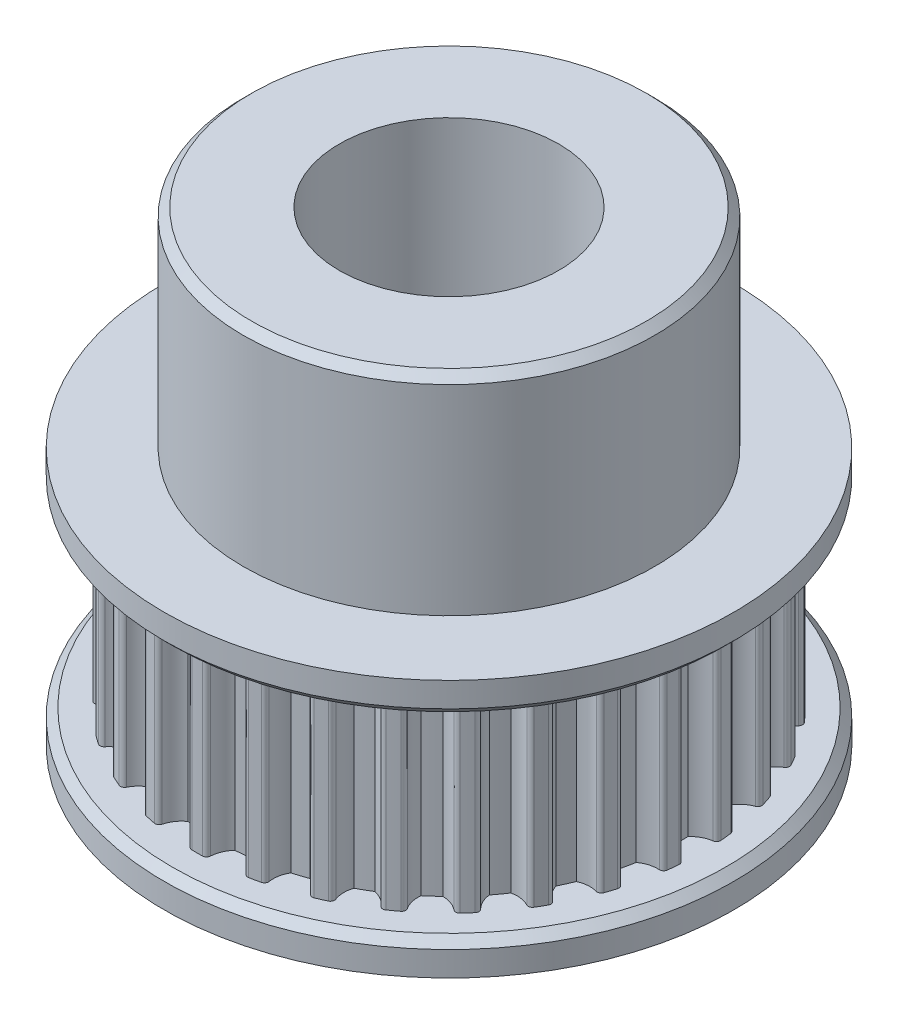
SolidWorks part; units mm, degrees
ref_plane "Front Plane" through (0, 0, 0) normal (0, 0, 1) x (1, 0, 0)
ref_plane "Top Plane" through (0, 0, 0) normal (0, 1, 0) x (1, 0, 0)
ref_plane "Right Plane" through (0, 0, 0) normal (1, 0, 0) x (0, 0, -1)
sketch "Sketch1" plane through (0, 0, 0) normal (0, 1, 0) x (1, 0, 0)
  line L0 (0, 0) -> (0, 9.44) construction
  line L1 (0, 0) -> (0.9867, 9.3883) construction
  line L2 (0, 0) -> (1.379, 9.3387) construction
  circle A0 centre (0, 0) radius 9.44 construction
  circle A1 centre (0, 0) radius 8.436 construction
  circle A2 centre (0, 0) radius 9.186 construction
  arc A3 (0.8818, 8.3898) -> (0.418, 8.7527) centre (0.9398, 8.9417) cw
  arc A4 (2.2821, 9.4281) -> (0.343, 9.0409) centre (1.3419, 9.0875) cw
  circle A5 centre (0, 0) radius 9.036 construction
  arc A6 (-0.1964, 9.1839) -> (0.1964, 9.1839) centre (0, 0) cw
  arc A7 (0.1964, 9.1839) -> (0.343, 9.0409) centre (0.1932, 9.0339) cw
  arc A8 (2.2821, 9.4281) -> (0.418, 8.7527) centre (1.3501, 9.0904) ccw
  arc A9 (-0.8818, 8.3898) -> (-0.418, 8.7527) centre (-0.9398, 8.9417) ccw
  arc A10 (-2.2821, 9.4281) -> (-0.418, 8.7527) centre (-1.3501, 9.0904) cw
  arc A11 (-2.2821, 9.4281) -> (-0.343, 9.0409) centre (-1.3419, 9.0875) ccw
  arc A12 (-0.1964, 9.1839) -> (-0.343, 9.0409) centre (-0.1932, 9.0339) ccw
  arc A13 (-0.8818, 8.3898) -> (0.8818, 8.3898) centre (0, 0) cw
  point P13 (1.3419, 9.0875)
  point P16 (0, 9.186)
  dimension "D1" = 18.88
  dimension "D6" = 0.555
  dimension "D7" = 1
  dimension "D9" = 0.15
  dimension "D2" = 6
  dimension "D3" = 2.4
  dimension "D4" = 1.004
  dimension "D5" = 0.75
  dimension "D8" = 0.15
extrude "Boss-Extrude1" add sketch "Sketch1" along normal blind 7 contours A9 A13 A3 A8 A4 A7 A6 A12 A11 A10
sketch "Sketch2" plane through (0, 0, 0) normal (0, -1, 0) x (1, 0, 0)
  circle A0 centre (0, 0) radius 8.436
  arc A2 (-0.6023, -8.4145) -> (0.6023, -8.4145) centre (0, 0) ccw construction
  arc A5 (-0.6023, -8.4145) -> (0.6023, -8.4145) centre (0, 0) ccw
extrude "Boss-Extrude2" add sketch "Sketch2" against normal blind 7
pattern_circular "CirPattern3" count 30 over 360 about axis through (0, 0, 0) along (0, 1, 0) of "Boss-Extrude1"
sketch "Sketch3" plane through (0, 7, 0) normal (0, 1, 0) x (1, 0, 0)
  circle A0 centre (0, 0) radius 10.386
  arc A3 (0.222, 10.3836) -> (-0.222, 10.3836) centre (0, 0) ccw
  arc A4 (0.222, 10.3836) -> (-0.222, 10.3836) centre (0, 0) ccw
  dimension "D1" = 1.2
extrude "Boss-Extrude3" add sketch "Sketch3" along normal blind 1.2 contours A0
sketch "Sketch4" plane through (0, 0, 0) normal (0, -1, 0) x (1, 0, 0)
  circle A0 centre (0, 0) radius 10.386 construction
  circle A1 centre (0, 0) radius 10.386
extrude "Boss-Extrude4" add sketch "Sketch4" along normal blind 1.2
sketch "Sketch12" plane through (0, 8.2, 0) normal (0, 1, 0) x (1, 0, 0)
  circle A0 centre (0, 0) radius 7.5
  dimension "D1" = 15
extrude "Boss-Extrude10" add sketch "Sketch12" along normal offset from surface (7.6 mm away) 17 up to face at (0, -1.2, -10.386)
sketch "Sketch5" plane through (0, 8.2, 0) normal (0, 1, 0) x (1, 0, 0)
  circle A0 centre (0, 0) radius 4
  dimension "D1" = 8
extrude "Cut-Extrude1" cut sketch "Sketch5" against normal through all both and the other way through all
chamfer "Chamfer1" distance 0.3 angle 45 3 edges at (0, 7, 10.386) (0, 0, -10.386) (0, 15.8, -7.5)
equation "\"TeethNumber\"=30"
equation "\"Pitch\"= 2"
equation "\"PulleyDiameter\"= \"TeethNumber\" * \"Pitch\" / PI"
equation "\"ToothAngle\"= ( 360 / \"TeethNumber\" )"
equation "\"TransOffsetAngle\"= \"ToothAngle\" * 0.2' "
equation "\"ShoulderRadius\"= 0.15"
equation "\"RootRadius\"= 0.555"
equation "\"TransRadius\"= 1"
equation "\"ToothHeight\"= 0.75"
equation "\"PLD\"= 0.254"
equation "\"D2@Sketch1\"=\"ToothAngle\"/2"
equation "\"D3@Sketch1\"=\"TransOffsetAngle\""
equation "\"D4@Sketch1\"=\"PLD\"+\"ToothHeight\""
equation "\"D5@Sketch1\"=\"ToothHeight\""
equation "\"D6@Sketch1\" = \"RootRadius\""
equation "\"D7@Sketch1\"=\"TransRadius\""
equation "\"D9@Sketch1\"=\"ShoulderRadius\""
equation "\"TeethNumber-2\"= 23"
equation "\"PulleyDiameter-2\"= \"TeethNumber-2\" * \"Pitch\" / PI"
equation "\"ToothAngle-2\"= 360/\"TeethNumber-2\""
equation "\"TransOffsetAngle-2\"= \"ToothAngle-2\" * 0.2"
equation "\"D1@CirPattern3\"=\"TeethNumber\""
equation "\"D1\"= \"TeethNumber-2\""
